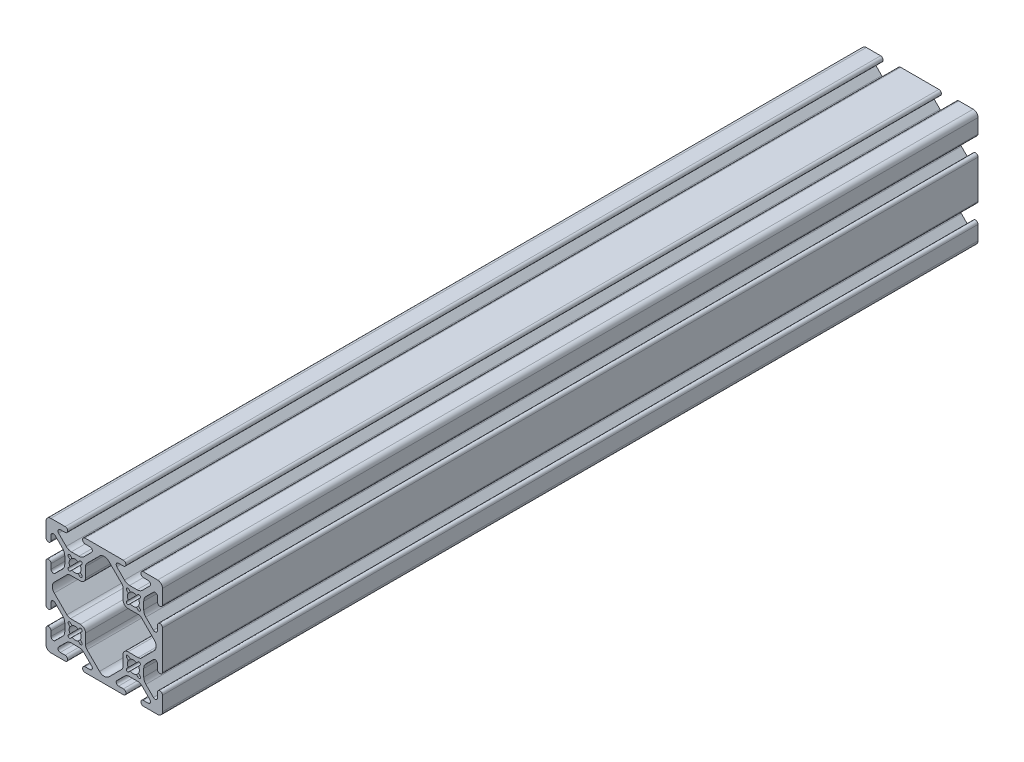
SolidWorks part; units mm, degrees
material "6105-T5 Aluminum"
ref_plane "Front Plane" through (0, 0, 0) normal (0, 0, 1) x (1, 0, 0)
ref_plane "Top Plane" through (0, 0, 0) normal (0, 1, 0) x (1, 0, 0)
ref_plane "Right Plane" through (0, 0, 0) normal (1, 0, 0) x (0, 0, -1)
sketch "Sketch1" plane through (0, 0, 0) normal (0, 0, 1) x (1, 0, 0)
  line L0 (-14.6692, 15.5605) -> (-14.0405, 14.9319)
  line L1 (-11.3595, 14.9319) -> (-10.7308, 15.5605)
  line L2 (-9.8395, 14.6692) -> (-10.4681, 14.0405)
  line L3 (-10.4681, 11.3595) -> (-9.8395, 10.7308)
  line L4 (-10.7308, 9.8395) -> (-11.3595, 10.4681)
  line L5 (-14.0405, 10.4681) -> (-14.6692, 9.8395)
  line L6 (-15.5605, 10.7308) -> (-14.9319, 11.3595)
  line L7 (-14.9319, 14.0405) -> (-15.5605, 14.6692)
  line L8 (11.3595, 10.4681) -> (10.7308, 9.8395)
  line L9 (9.8395, 10.7308) -> (10.4681, 11.3595)
  line L10 (10.4681, 14.0405) -> (9.8395, 14.6692)
  line L11 (10.7308, 15.5605) -> (11.3595, 14.9319)
  line L12 (14.0405, 14.9319) -> (14.6692, 15.5605)
  line L13 (15.5605, 14.6692) -> (14.9319, 14.0405)
  line L14 (14.9319, 11.3595) -> (15.5605, 10.7308)
  line L15 (14.6692, 9.8395) -> (14.0405, 10.4681)
  line L16 (-14.6692, -9.8395) -> (-14.0405, -10.4681)
  line L17 (-11.3595, -10.4681) -> (-10.7308, -9.8395)
  line L18 (-9.8395, -10.7308) -> (-10.4681, -11.3595)
  line L19 (-10.4681, -14.0405) -> (-9.8395, -14.6692)
  line L20 (-10.7308, -15.5605) -> (-11.3595, -14.9319)
  line L21 (-14.0405, -14.9319) -> (-14.6692, -15.5605)
  line L22 (-15.5605, -14.6692) -> (-14.9319, -14.0405)
  line L23 (-14.9319, -11.3595) -> (-15.5605, -10.7308)
  line L24 (10.7308, -9.8395) -> (11.3595, -10.4681)
  line L25 (14.0405, -10.4681) -> (14.6692, -9.8395)
  line L26 (15.5605, -10.7308) -> (14.9319, -11.3595)
  line L27 (14.9319, -14.0405) -> (15.5605, -14.6692)
  line L28 (14.6692, -15.5605) -> (14.0405, -14.9319)
  line L29 (11.3595, -14.9319) -> (10.7308, -15.5605)
  line L30 (9.8395, -14.6692) -> (10.4681, -14.0405)
  line L31 (10.4681, -11.3595) -> (9.8395, -10.7308)
  line L32 (7.5356, -16.3017) -> (2.0587, -21.7787)
  line L33 (-2.0587, -21.7787) -> (-7.5356, -16.3017)
  line L34 (-8.1828, -14.7392) -> (-8.1828, -10.3926)
  line L35 (-10.3926, -8.1828) -> (-14.7392, -8.1828)
  line L36 (-16.3017, -7.5356) -> (-21.7787, -2.0587)
  line L37 (-21.7787, 2.0587) -> (-16.3017, 7.5356)
  line L38 (-14.7392, 8.1828) -> (-10.3926, 8.1828)
  line L39 (-8.1828, 10.3926) -> (-8.1828, 14.7392)
  line L40 (-7.5356, 16.3017) -> (-2.0587, 21.7787)
  line L41 (2.0587, 21.7787) -> (7.5356, 16.3017)
  line L42 (8.1828, 14.7392) -> (8.1828, 10.3926)
  line L43 (10.3926, 8.1828) -> (14.7392, 8.1828)
  line L44 (16.3017, 7.5356) -> (21.7787, 2.0587)
  line L45 (21.7787, -2.0587) -> (16.3017, -7.5356)
  line L46 (14.7392, -8.1828) -> (10.3926, -8.1828)
  line L47 (8.1828, -10.3926) -> (8.1828, -14.7392)
  line L48 (25.4, 17.0561) -> (25.4, 23.2918)
  line L49 (23.2918, 25.4) -> (17.0561, 25.4)
  line L50 (17.0561, 23.1902) -> (19.1749, 23.1902)
  line L51 (19.8933, 21.4558) -> (16.5846, 18.1471)
  line L52 (14.3396, 17.2172) -> (11.0604, 17.2172)
  line L53 (8.8154, 18.1471) -> (5.5067, 21.4558)
  line L54 (6.2251, 23.1902) -> (8.3439, 23.1902)
  line L55 (8.3439, 25.4) -> (-8.3439, 25.4)
  line L56 (-8.3439, 23.1902) -> (-6.2251, 23.1902)
  line L57 (-5.5067, 21.4558) -> (-8.8154, 18.1471)
  line L58 (-11.0604, 17.2172) -> (-14.3396, 17.2172)
  line L59 (-16.5846, 18.1471) -> (-19.8933, 21.4558)
  line L60 (-19.1749, 23.1902) -> (-17.0561, 23.1902)
  line L61 (-17.0561, 25.4) -> (-23.2918, 25.4)
  line L62 (-25.4, 23.2918) -> (-25.4, 17.0561)
  line L63 (-23.1902, 17.0561) -> (-23.1902, 19.1749)
  line L64 (-21.4558, 19.8933) -> (-18.1471, 16.5846)
  line L65 (-17.2172, 14.3396) -> (-17.2172, 11.0604)
  line L66 (-18.1471, 8.8154) -> (-21.4558, 5.5067)
  line L67 (-23.1902, 6.2251) -> (-23.1902, 8.3439)
  line L68 (-25.4, 8.3439) -> (-25.4, -8.3439)
  line L69 (-23.1902, -8.3439) -> (-23.1902, -6.2251)
  line L70 (-21.4558, -5.5067) -> (-18.1471, -8.8154)
  line L71 (-17.2172, -11.0604) -> (-17.2172, -14.3396)
  line L72 (-18.1471, -16.5846) -> (-21.4558, -19.8933)
  line L73 (-23.1902, -19.1749) -> (-23.1902, -17.0561)
  line L74 (-25.4, -17.0561) -> (-25.4, -23.2918)
  line L75 (-23.2918, -25.4) -> (-17.0561, -25.4)
  line L76 (-17.0561, -23.1902) -> (-19.1749, -23.1902)
  line L77 (-19.8933, -21.4558) -> (-16.5846, -18.1471)
  line L78 (-14.3396, -17.2172) -> (-11.0604, -17.2172)
  line L79 (-8.8154, -18.1471) -> (-5.5067, -21.4558)
  line L80 (-6.2251, -23.1902) -> (-8.3439, -23.1902)
  line L81 (-8.3439, -25.4) -> (8.3439, -25.4)
  line L82 (8.3439, -23.1902) -> (6.2251, -23.1902)
  line L83 (5.5067, -21.4558) -> (8.8154, -18.1471)
  line L84 (11.0604, -17.2172) -> (14.3396, -17.2172)
  line L85 (16.5846, -18.1471) -> (19.8933, -21.4558)
  line L86 (19.1749, -23.1902) -> (17.0561, -23.1902)
  line L87 (17.0561, -25.4) -> (23.2918, -25.4)
  line L88 (25.4, -23.2918) -> (25.4, -17.0561)
  line L89 (23.1902, -17.0561) -> (23.1902, -19.1749)
  line L90 (21.4558, -19.8933) -> (18.1471, -16.5846)
  line L91 (17.2172, -14.3396) -> (17.2172, -11.0604)
  line L92 (18.1471, -8.8154) -> (21.4558, -5.5067)
  line L93 (23.1902, -6.2251) -> (23.1902, -8.3439)
  line L94 (25.4, -8.3439) -> (25.4, 8.3439)
  line L95 (23.1902, 8.3439) -> (23.1902, 6.2251)
  line L96 (21.4558, 5.5067) -> (18.1471, 8.8154)
  line L97 (17.2172, 11.0604) -> (17.2172, 14.3396)
  line L98 (18.1471, 16.5846) -> (21.4558, 19.8933)
  line L99 (23.1902, 19.1749) -> (23.1902, 17.0561)
  arc A0 (-11.3595, 14.9319) -> (-14.0405, 14.9319) centre (-12.7, 12.7) ccw
  arc A1 (-9.8395, 14.6692) -> (-10.7308, 15.5605) centre (-10.2304, 15.1696) ccw
  arc A2 (-10.4681, 11.3595) -> (-10.4681, 14.0405) centre (-12.7, 12.7) ccw
  arc A3 (-10.7308, 9.8395) -> (-9.8395, 10.7308) centre (-10.2304, 10.2304) ccw
  arc A4 (-14.0405, 10.4681) -> (-11.3595, 10.4681) centre (-12.7, 12.7) ccw
  arc A5 (-15.5605, 10.7308) -> (-14.6692, 9.8395) centre (-15.1696, 10.2304) ccw
  arc A6 (-14.9319, 14.0405) -> (-14.9319, 11.3595) centre (-12.7, 12.7) ccw
  arc A7 (-14.6692, 15.5605) -> (-15.5605, 14.6692) centre (-15.1696, 15.1696) ccw
  arc A8 (9.8395, 10.7308) -> (10.7308, 9.8395) centre (10.2304, 10.2304) ccw
  arc A9 (10.4681, 14.0405) -> (10.4681, 11.3595) centre (12.7, 12.7) ccw
  arc A10 (10.7308, 15.5605) -> (9.8395, 14.6692) centre (10.2304, 15.1696) ccw
  arc A11 (14.0405, 14.9319) -> (11.3595, 14.9319) centre (12.7, 12.7) ccw
  arc A12 (15.5605, 14.6692) -> (14.6692, 15.5605) centre (15.1696, 15.1696) ccw
  arc A13 (14.9319, 11.3595) -> (14.9319, 14.0405) centre (12.7, 12.7) ccw
  arc A14 (14.6692, 9.8395) -> (15.5605, 10.7308) centre (15.1696, 10.2304) ccw
  arc A15 (11.3595, 10.4681) -> (14.0405, 10.4681) centre (12.7, 12.7) ccw
  arc A16 (-11.3595, -10.4681) -> (-14.0405, -10.4681) centre (-12.7, -12.7) ccw
  arc A17 (-9.8395, -10.7308) -> (-10.7308, -9.8395) centre (-10.2304, -10.2304) ccw
  arc A18 (-10.4681, -14.0405) -> (-10.4681, -11.3595) centre (-12.7, -12.7) ccw
  arc A19 (-10.7308, -15.5605) -> (-9.8395, -14.6692) centre (-10.2304, -15.1696) ccw
  arc A20 (-14.0405, -14.9319) -> (-11.3595, -14.9319) centre (-12.7, -12.7) ccw
  arc A21 (-15.5605, -14.6692) -> (-14.6692, -15.5605) centre (-15.1696, -15.1696) ccw
  arc A22 (-14.9319, -11.3595) -> (-14.9319, -14.0405) centre (-12.7, -12.7) ccw
  arc A23 (-14.6692, -9.8395) -> (-15.5605, -10.7308) centre (-15.1696, -10.2304) ccw
  arc A24 (14.0405, -10.4681) -> (11.3595, -10.4681) centre (12.7, -12.7) ccw
  arc A25 (15.5605, -10.7308) -> (14.6692, -9.8395) centre (15.1696, -10.2304) ccw
  arc A26 (14.9319, -14.0405) -> (14.9319, -11.3595) centre (12.7, -12.7) ccw
  arc A27 (14.6692, -15.5605) -> (15.5605, -14.6692) centre (15.1696, -15.1696) ccw
  arc A28 (11.3595, -14.9319) -> (14.0405, -14.9319) centre (12.7, -12.7) ccw
  arc A29 (9.8395, -14.6692) -> (10.7308, -15.5605) centre (10.2304, -15.1696) ccw
  arc A30 (10.4681, -11.3595) -> (10.4681, -14.0405) centre (12.7, -12.7) ccw
  arc A31 (10.7308, -9.8395) -> (9.8395, -10.7308) centre (10.2304, -10.2304) ccw
  arc A32 (-2.0587, -21.7787) -> (2.0587, -21.7787) centre (0, -19.72) ccw
  arc A33 (-8.1828, -14.7392) -> (-7.5356, -16.3017) centre (-5.973, -14.7392) ccw
  arc A34 (-8.1828, -10.3926) -> (-10.3926, -8.1828) centre (-10.3926, -10.3926) ccw
  arc A35 (-16.3017, -7.5356) -> (-14.7392, -8.1828) centre (-14.7392, -5.973) ccw
  arc A36 (-21.7787, 2.0587) -> (-21.7787, -2.0587) centre (-19.72, 0) ccw
  arc A37 (-14.7392, 8.1828) -> (-16.3017, 7.5356) centre (-14.7392, 5.973) ccw
  arc A38 (-10.3926, 8.1828) -> (-8.1828, 10.3926) centre (-10.3926, 10.3926) ccw
  arc A39 (-7.5356, 16.3017) -> (-8.1828, 14.7392) centre (-5.973, 14.7392) ccw
  arc A40 (2.0587, 21.7787) -> (-2.0587, 21.7787) centre (0, 19.72) ccw
  arc A41 (8.1828, 14.7392) -> (7.5356, 16.3017) centre (5.973, 14.7392) ccw
  arc A42 (8.1828, 10.3926) -> (10.3926, 8.1828) centre (10.3926, 10.3926) ccw
  arc A43 (16.3017, 7.5356) -> (14.7392, 8.1828) centre (14.7392, 5.973) ccw
  arc A44 (21.7787, -2.0587) -> (21.7787, 2.0587) centre (19.72, 0) ccw
  arc A45 (14.7392, -8.1828) -> (16.3017, -7.5356) centre (14.7392, -5.973) ccw
  arc A46 (10.3926, -8.1828) -> (8.1828, -10.3926) centre (10.3926, -10.3926) ccw
  arc A47 (7.5356, -16.3017) -> (8.1828, -14.7392) centre (5.973, -14.7392) ccw
  arc A48 (23.1902, 17.0561) -> (25.4, 17.0561) centre (24.2951, 17.0561) ccw
  arc A49 (25.4, 23.2918) -> (23.2918, 25.4) centre (23.2918, 23.2918) ccw
  arc A50 (17.0561, 25.4) -> (17.0561, 23.1902) centre (17.0561, 24.2951) ccw
  arc A51 (19.8933, 21.4558) -> (19.1749, 23.1902) centre (19.1749, 22.1742) ccw
  arc A52 (14.3396, 17.2172) -> (16.5846, 18.1471) centre (14.3396, 20.3922) ccw
  arc A53 (8.8154, 18.1471) -> (11.0604, 17.2172) centre (11.0604, 20.3922) ccw
  arc A54 (6.2251, 23.1902) -> (5.5067, 21.4558) centre (6.2251, 22.1742) ccw
  arc A55 (8.3439, 23.1902) -> (8.3439, 25.4) centre (8.3439, 24.2951) ccw
  arc A56 (-8.3439, 25.4) -> (-8.3439, 23.1902) centre (-8.3439, 24.2951) ccw
  arc A57 (-5.5067, 21.4558) -> (-6.2251, 23.1902) centre (-6.2251, 22.1742) ccw
  arc A58 (-11.0604, 17.2172) -> (-8.8154, 18.1471) centre (-11.0604, 20.3922) ccw
  arc A59 (-16.5846, 18.1471) -> (-14.3396, 17.2172) centre (-14.3396, 20.3922) ccw
  arc A60 (-19.1749, 23.1902) -> (-19.8933, 21.4558) centre (-19.1749, 22.1742) ccw
  arc A61 (-17.0561, 23.1902) -> (-17.0561, 25.4) centre (-17.0561, 24.2951) ccw
  arc A62 (-23.2918, 25.4) -> (-25.4, 23.2918) centre (-23.2918, 23.2918) ccw
  arc A63 (-25.4, 17.0561) -> (-23.1902, 17.0561) centre (-24.2951, 17.0561) ccw
  arc A64 (-21.4558, 19.8933) -> (-23.1902, 19.1749) centre (-22.1742, 19.1749) ccw
  arc A65 (-17.2172, 14.3396) -> (-18.1471, 16.5846) centre (-20.3922, 14.3396) ccw
  arc A66 (-18.1471, 8.8154) -> (-17.2172, 11.0604) centre (-20.3922, 11.0604) ccw
  arc A67 (-23.1902, 6.2251) -> (-21.4558, 5.5067) centre (-22.1742, 6.2251) ccw
  arc A68 (-23.1902, 8.3439) -> (-25.4, 8.3439) centre (-24.2951, 8.3439) ccw
  arc A69 (-25.4, -8.3439) -> (-23.1902, -8.3439) centre (-24.2951, -8.3439) ccw
  arc A70 (-21.4558, -5.5067) -> (-23.1902, -6.2251) centre (-22.1742, -6.2251) ccw
  arc A71 (-17.2172, -11.0604) -> (-18.1471, -8.8154) centre (-20.3922, -11.0604) ccw
  arc A72 (-18.1471, -16.5846) -> (-17.2172, -14.3396) centre (-20.3922, -14.3396) ccw
  arc A73 (-23.1902, -19.1749) -> (-21.4558, -19.8933) centre (-22.1742, -19.1749) ccw
  arc A74 (-23.1902, -17.0561) -> (-25.4, -17.0561) centre (-24.2951, -17.0561) ccw
  arc A75 (-25.4, -23.2918) -> (-23.2918, -25.4) centre (-23.2918, -23.2918) ccw
  arc A76 (-17.0561, -25.4) -> (-17.0561, -23.1902) centre (-17.0561, -24.2951) ccw
  arc A77 (-19.8933, -21.4558) -> (-19.1749, -23.1902) centre (-19.1749, -22.1742) ccw
  arc A78 (-14.3396, -17.2172) -> (-16.5846, -18.1471) centre (-14.3396, -20.3922) ccw
  arc A79 (-8.8154, -18.1471) -> (-11.0604, -17.2172) centre (-11.0604, -20.3922) ccw
  arc A80 (-6.2251, -23.1902) -> (-5.5067, -21.4558) centre (-6.2251, -22.1742) ccw
  arc A81 (-8.3439, -23.1902) -> (-8.3439, -25.4) centre (-8.3439, -24.2951) ccw
  arc A82 (8.3439, -25.4) -> (8.3439, -23.1902) centre (8.3439, -24.2951) ccw
  arc A83 (5.5067, -21.4558) -> (6.2251, -23.1902) centre (6.2251, -22.1742) ccw
  arc A84 (11.0604, -17.2172) -> (8.8154, -18.1471) centre (11.0604, -20.3922) ccw
  arc A85 (16.5846, -18.1471) -> (14.3396, -17.2172) centre (14.3396, -20.3922) ccw
  arc A86 (19.1749, -23.1902) -> (19.8933, -21.4558) centre (19.1749, -22.1742) ccw
  arc A87 (17.0561, -23.1902) -> (17.0561, -25.4) centre (17.0561, -24.2951) ccw
  arc A88 (23.2918, -25.4) -> (25.4, -23.2918) centre (23.2918, -23.2918) ccw
  arc A89 (25.4, -17.0561) -> (23.1902, -17.0561) centre (24.2951, -17.0561) ccw
  arc A90 (21.4558, -19.8933) -> (23.1902, -19.1749) centre (22.1742, -19.1749) ccw
  arc A91 (17.2172, -14.3396) -> (18.1471, -16.5846) centre (20.3922, -14.3396) ccw
  arc A92 (18.1471, -8.8154) -> (17.2172, -11.0604) centre (20.3922, -11.0604) ccw
  arc A93 (23.1902, -6.2251) -> (21.4558, -5.5067) centre (22.1742, -6.2251) ccw
  arc A94 (23.1902, -8.3439) -> (25.4, -8.3439) centre (24.2951, -8.3439) ccw
  arc A95 (25.4, 8.3439) -> (23.1902, 8.3439) centre (24.2951, 8.3439) ccw
  arc A96 (21.4558, 5.5067) -> (23.1902, 6.2251) centre (22.1742, 6.2251) ccw
  arc A97 (17.2172, 11.0604) -> (18.1471, 8.8154) centre (20.3922, 11.0604) ccw
  arc A98 (18.1471, 16.5846) -> (17.2172, 14.3396) centre (20.3922, 14.3396) ccw
  arc A99 (23.1902, 19.1749) -> (21.4558, 19.8933) centre (22.1742, 19.1749) ccw
extrude "Extrude1" add sketch "Sketch1" against normal blind 355.6
